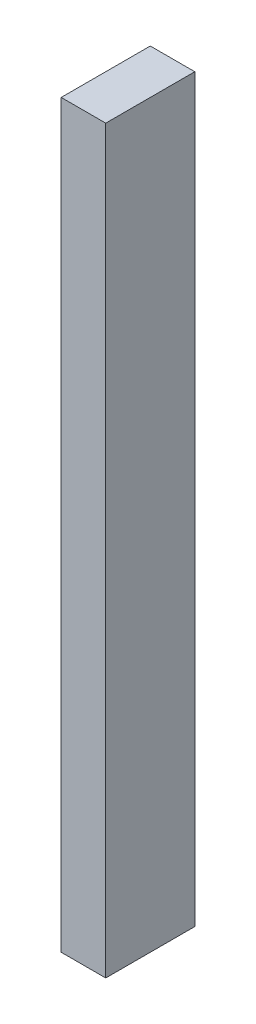
SolidWorks part; units mm, degrees
ref_plane "Front" through (0, 0, 0) normal (0, 0, 1) x (1, 0, 0)
ref_plane "Top" through (0, 0, 0) normal (0, 1, 0) x (1, 0, 0)
ref_plane "Right" through (0, 0, 0) normal (1, 0, 0) x (0, 0, -1)
sketch "Эскиз1" plane through (0, 0, 0) normal (1, 0, 0) x (0, 0, -1)
  line L2 (405.8761, 643.5354) -> (405.8761, 311.0354)
  line L3 (405.8761, 311.0354) -> (365.8761, 311.0354)
  line L4 (365.8761, 643.5354) -> (365.8761, 311.0354)
  line L8 (365.8761, 643.5354) -> (405.8761, 643.5354)
  dimension "D1" = 332.5
  dimension "D2" = 40
extrude "Бобышка-Вытянуть1" add sketch "Эскиз1" along normal blind 20
